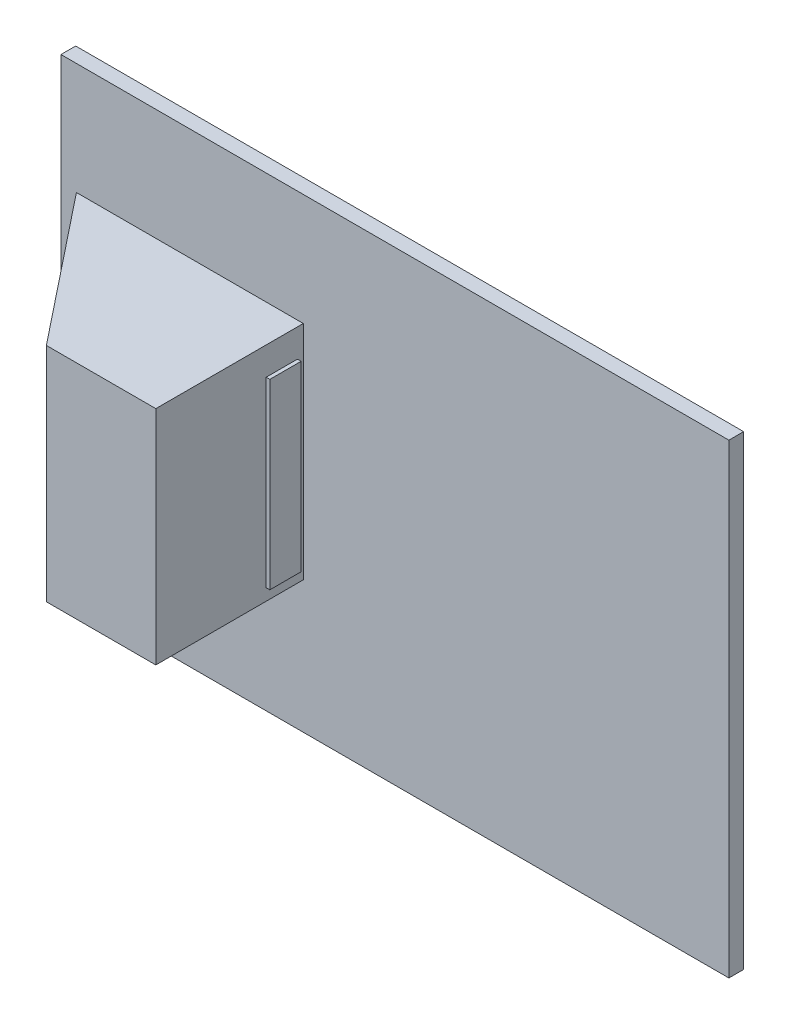
SolidWorks part; units mm, degrees
ref_plane "Front Plane" through (0, 0, 0) normal (0, 0, 1) x (1, 0, 0)
ref_plane "Top Plane" through (0, 0, 0) normal (0, 1, 0) x (1, 0, 0)
ref_plane "Right Plane" through (0, 0, 0) normal (1, 0, 0) x (0, 0, -1)
sketch "Sketch1" plane through (0, 0, 0) normal (0, 0, 1) x (1, 0, 0)
  line L1 (-83.6964, -45.2831) -> (2.5697, -45.2831)
  line L2 (-83.6964, -45.2831) -> (-83.6964, 12.5794)
  line L3 (-83.6964, 12.5794) -> (2.5697, 12.5794)
  line L4 (2.5697, -45.2831) -> (2.5697, 12.5794)
  line L5 (-83.6964, -45.2831) -> (2.5697, 12.5794) construction
  line L6 (-83.6964, 12.5794) -> (2.5697, -45.2831) construction
  point P0 (-40.5634, -16.3519)
  point P5 (2.5697, -48.5767)
extrude "Boss-Extrude1" add sketch "Sketch1" along normal blind 5
sketch "Sketch2" plane through (0, 0, 0) normal (0, 0, -1) x (-1, 0, 0)
  line L1 (50.5486, -38.5474) -> (14.2877, -38.5474)
  line L2 (50.5486, -38.5474) -> (50.5486, 6.6921)
  line L3 (50.5486, 6.6921) -> (14.2877, 6.6921)
  line L4 (14.2877, -38.5474) -> (14.2877, 6.6921)
  line L5 (50.5486, -38.5474) -> (14.2877, 6.6921) construction
  line L6 (50.5486, 6.6921) -> (14.2877, -38.5474) construction
  line L7 (49.8095, -37.7028) -> (15.0267, -37.7028)
  line L8 (49.8095, -37.7028) -> (49.8095, 5.8475)
  line L9 (49.8095, 5.8475) -> (15.0267, 5.8475)
  line L10 (15.0267, -37.7028) -> (15.0267, 5.8475)
  line L11 (49.8095, -37.7028) -> (15.0267, 5.8475) construction
  line L12 (49.8095, 5.8475) -> (15.0267, -37.7028) construction
  point P0 (32.4181, -15.9276)
  point P5 (29.0156, -12.5739)
  point P6 (32.4181, -15.9276)
  point P11 (31.5127, -12.7779)
  point P12 (31.8702, -14.0102)
  point P13 (32.3017, -17.6957)
  point P14 (32.6138, -14.9651)
  point P15 (32.4181, -15.9276)
extrude "Boss-Extrude2" add sketch "Sketch2" along normal blind 1
sketch "Sketch3" plane through (0, 0, 0) normal (0, 0, -1) x (-1, 0, 0)
  circle A0 centre (5.8472, -15.8094) radius 3.5601
  point P2 (0, 0)
extrude "Boss-Extrude3" add sketch "Sketch3" along normal blind 1
sketch "Sketch4" plane through (0, 0, -1) normal (0, 0, -1) x (-1, 0, 0)
  line L0 (7.4982, -13.5037) -> (7.4299, -14.2268)
  line L1 (7.3138, -18.3414) -> (7.3192, -17.6008)
  arc A0 (7.4982, -13.5037) -> (7.3138, -18.3414) centre (5.955, -15.8672) ccw
  arc A1 (7.4299, -14.2268) -> (7.3192, -17.6008) centre (5.955, -15.8672) ccw
  point P1 (0, 0)
extrude "Cut-Extrude2" cut sketch "Sketch4" against normal blind 0.5
sketch "Sketch5" plane through (0, 0, -1) normal (0, 0, -1) x (-1, 0, 0)
  line L0 (8.3401, -15.4929) -> (5.464, -15.4382)
  line L1 (8.3401, -16.1787) -> (5.464, -16.2334)
  arc A0 (8.3401, -16.1787) -> (8.3401, -15.4929) centre (8.3401, -15.8358) ccw
  arc A1 (5.464, -15.4382) -> (5.464, -16.2334) centre (5.464, -15.8358) ccw
extrude "Cut-Extrude3" cut sketch "Sketch5" against normal blind 0.5
sketch "Sketch11" plane through (0, 0, 5) normal (0, 0, 1) x (1, 0, 0)
  line L1 (-85.049, -48.3572) -> (5.5329, -48.3572)
  line L2 (-85.049, -48.3572) -> (-85.049, 14.8126)
  line L3 (-85.049, 14.8126) -> (5.5329, 14.8126)
  line L4 (5.5329, -48.3572) -> (5.5329, 14.8126)
  line L5 (-85.049, -48.3572) -> (5.5329, 14.8126) construction
  line L6 (-85.049, 14.8126) -> (5.5329, -48.3572) construction
  point P0 (-39.7581, -16.7723)
extrude "Boss-Extrude4" add sketch "Sketch11" along normal blind 2
sketch "Sketch12" plane through (2.5697, 0, 0) normal (1, 0, 0) x (0, 0, -1)
  line L0 (-5.0495, 12.5555) -> (1.3768, 8.6378)
  line L1 (1.3768, 8.6378) -> (1.4949, 17.885)
  line L2 (1.4949, 17.885) -> (-5.0495, 12.5555)
  point P0 (-5.0495, 12.5555)
extrude "Cut-Extrude11" cut sketch "Sketch12" against normal through all
sketch "Sketch14" plane through (-85.049, 0, 0) normal (-1, 0, 0) x (0, 0, 1)
  line L0 (5, -45.2349) -> (-1.3308, -41.1782)
  line L1 (5, 12.5253) -> (5, -48.3572) construction
  line L2 (-1.3308, -41.1782) -> (-1.6233, -49.506)
  line L3 (-1.6233, -49.506) -> (5, -45.2349)
  point P4 (5, -45.2349)
extrude "Cut-Extrude15" cut sketch "Sketch14" against normal through all
sketch "Sketch15" plane through (0, -48.3572, 0) normal (0, -1, 0) x (-1, 0, 0)
  line L0 (-2.5596, -5) -> (1.7788, 1.2395)
  line L1 (85.049, -5) -> (-5.5329, -5) construction
  line L2 (1.7788, 1.2395) -> (-4.0713, 1.1275)
  line L3 (-4.0713, 1.1275) -> (-2.5596, -5)
  point P4 (-2.5263, -5)
  point P8 (-2.5596, -5)
extrude "Cut-Extrude18" cut sketch "Sketch15" against normal through all
sketch "Sketch19" plane through (0, -48.3572, 0) normal (0, -1, 0) x (-1, 0, 0)
  line L0 (83.7172, -5) -> (87.2746, 1.6454)
  line L1 (85.049, -5) -> (-5.5329, -5) construction
  line L2 (87.2746, 1.6454) -> (78.5287, 2.7469)
  line L3 (78.5287, 2.7469) -> (83.7172, -5)
extrude "Cut-Extrude21" cut sketch "Sketch19" against normal through all
sketch "Sketch22" plane through (0, 0, 7) normal (0, 0, 1) x (1, 0, 0)
  line L1 (-82.9526, -0.3433) -> (-52.184, -0.3433)
  line L2 (-82.9526, -0.3433) -> (-82.9526, -30.4515)
  line L3 (-82.9526, -30.4515) -> (-52.184, -30.4515)
  line L4 (-52.184, -0.3433) -> (-52.184, -30.4515)
  line L5 (-82.9526, -0.3433) -> (-52.184, -30.4515) construction
  line L6 (-82.9526, -30.4515) -> (-52.184, -0.3433) construction
  point P0 (-67.5683, -15.3974)
extrude "Boss-Extrude9" add sketch "Sketch22" along normal blind 20
sketch "Sketch23" plane through (-55.4815, 0, -37.1587) normal (-0.8309, 0, -0.5565) x (-0.5565, 0, 0.8309)
  line L0 (50.7032, -28.438) -> (50.7032, -4.3391)
  line L1 (50.7032, 12.5064) -> (50.7032, -45.2151) construction
  line L2 (50.7032, -4.3391) -> (35.7393, -4.3391)
  line L3 (35.7393, -4.3391) -> (35.7393, -28.6863)
  line L4 (35.7393, -28.6863) -> (50.7032, -28.438)
  point P4 (39.3795, -28.6259)
extrude "Cut-Extrude25" cut sketch "Sketch23" against normal blind 30
sketch "Sketch24" plane through (0, 0, 0) normal (0, 0, -1) x (-1, 0, 0)
  line L0 (80.3685, -4.3391) -> (64.2248, -4.3391) construction
  line L1 (53.8212, -28.6863) -> (64.2248, -28.6863)
  line L2 (53.8212, -28.6863) -> (53.8212, -4.3391)
  line L3 (53.8212, -4.3391) -> (64.2248, -4.3391)
  line L4 (64.2248, -28.6863) -> (64.2248, -4.3391)
  line L5 (53.8212, -28.6863) -> (64.2248, -4.3391) construction
  line L6 (53.8212, -4.3391) -> (64.2248, -28.6863) construction
  line L7 (64.2248, -4.3391) -> (64.2248, -28.6863) construction
  point P0 (59.023, -16.5127)
extrude "Cut-Extrude27" cut sketch "Sketch24" against normal blind 7
sketch "Sketch25" plane through (0, -30.4515, 0) normal (0, -1, 0) x (-1, 0, 0)
  line L0 (67.027, -27) -> (82.9526, -7)
  line L1 (82.9526, -27) -> (52.184, -27) construction
  line L2 (82.9526, -7) -> (82.9526, -27)
  line L3 (82.9526, -27) -> (82.9526, -7) construction
  line L4 (82.9526, -27) -> (67.027, -27)
  point P5 (82.9526, -27)
extrude "Cut-Extrude29" cut sketch "Sketch25" against normal through all
sketch "Sketch26" plane through (-28.2149, 0, 42.1276) normal (0.5565, 0, -0.8309) x (-0.8309, 0, -0.5565)
  line L0 (54.7061, -26.9497) -> (51.42, -27.0426)
  line L1 (51.42, -27.0426) -> (49.1981, -24.943)
  line L2 (49.1981, -24.943) -> (49.1134, -21.9477)
  line L3 (49.1134, -21.9477) -> (51.379, -19.9792)
  line L4 (51.379, -19.9792) -> (54.3761, -19.7757)
  line L5 (54.3761, -19.7757) -> (56.7869, -21.3756)
  line L6 (56.7869, -21.3756) -> (56.7869, -24.7523)
  line L7 (56.7869, -24.7523) -> (54.7061, -26.9497)
  line L8 (54.7061, -26.4154) -> (51.5118, -26.5172)
  line L9 (51.5118, -26.5172) -> (49.6724, -24.7913)
  line L10 (49.6724, -24.7913) -> (49.5843, -22.0272)
  line L11 (49.5843, -22.0272) -> (51.5118, -20.3421)
  line L13 (54.292, -20.113) -> (56.4421, -21.5046)
  line L14 (56.4421, -21.5046) -> (56.4421, -24.6328)
  line L15 (56.4421, -24.6328) -> (54.7061, -26.4154)
  line L16 (54.292, -20.113) -> (51.4865, -20.3421)
extrude "Boss-Extrude12" add sketch "Sketch26" along normal blind 0.5
sketch "Sketch27" plane through (-27.9367, 0, 41.7122) normal (0.5565, 0, -0.8309) x (-0.8309, 0, -0.5565)
  line L0 (54.4646, -26.3342) -> (51.6468, -26.4613)
  line L1 (51.6468, -26.4613) -> (49.7838, -24.7591)
  line L2 (49.7838, -24.7591) -> (49.7838, -22.033)
  line L3 (49.7838, -22.033) -> (51.4884, -20.6267)
  line L4 (51.4884, -20.6267) -> (54.0987, -20.567)
  line L5 (54.0987, -20.567) -> (56.1639, -21.7042)
  line L6 (56.1639, -21.7042) -> (56.2319, -24.6811)
  line L7 (56.2319, -24.6811) -> (54.4646, -26.3342)
  line L8 (54.3202, -25.7184) -> (51.7276, -25.7776)
  line L9 (51.7276, -25.7776) -> (50.5704, -24.5406)
  line L10 (50.5704, -24.5406) -> (50.4628, -22.1543)
  line L11 (50.4628, -22.1543) -> (51.4425, -21.2379)
  line L12 (51.4425, -21.2379) -> (54.0133, -21.2379)
  line L13 (54.0133, -21.2379) -> (55.475, -22.0626)
  line L14 (55.475, -22.0626) -> (55.475, -24.5406)
  line L15 (55.475, -24.5406) -> (54.3202, -25.7184)
  point P11 (55.6709, -24.7402)
  point P17 (51.4521, -21.229)
  point P18 (54.0133, -21.2379)
  point P19 (50.5704, -24.5406)
extrude "Cut-Extrude30" cut sketch "Sketch27" against normal blind 0.5
sketch "Sketch28" plane through (-52.184, 0, 0) normal (1, 0, 0) x (0, 0, -1)
  line L1 (-7.7943, -4.1368) -> (-12.0375, -4.1368)
  line L2 (-7.7943, -4.1368) -> (-7.7943, -28.8565)
  line L3 (-7.7943, -28.8565) -> (-12.0375, -28.8565)
  line L4 (-12.0375, -4.1368) -> (-12.0375, -28.8565)
  line L5 (-7.7943, -4.1368) -> (-12.0375, -28.8565) construction
  line L6 (-7.7943, -28.8565) -> (-12.0375, -4.1368) construction
  point P0 (-9.9159, -16.4967)
extrude "Boss-Extrude13" add sketch "Sketch28" along normal blind 0.5
sketch "Sketch30" plane through (-28.2149, 0, 42.1276) normal (0.5565, 0, -0.8309) x (-0.8309, 0, -0.5565)
  line L0 (39.741, -18.4923) -> (39.4768, -15.4766)
  line L1 (39.4768, -15.4766) -> (41.6727, -13.4395)
  line L2 (41.6727, -13.4395) -> (44.994, -13.0953)
  line L3 (44.994, -13.0953) -> (47.5825, -14.9189)
  line L4 (47.5825, -14.9189) -> (47.5825, -17.5566)
  line L5 (47.5825, -17.5566) -> (45.5971, -19.8398)
  line L6 (45.5971, -19.8398) -> (42.2786, -20.1305)
  line L7 (42.2786, -20.1305) -> (39.741, -18.4923)
  line L8 (42.7534, -19.5576) -> (40.2187, -17.9152)
  line L9 (40.2187, -17.9152) -> (40.0475, -15.6187)
  line L10 (40.0475, -15.6187) -> (41.8581, -13.9959)
  line L11 (41.8581, -13.9959) -> (44.6411, -13.7001)
  line L12 (44.6411, -13.7001) -> (47.0086, -15.2342)
  line L13 (47.0086, -15.2342) -> (47.0876, -17.3469)
  line L14 (47.0876, -17.3469) -> (45.2147, -19.3741)
  line L15 (45.2147, -19.3741) -> (42.7534, -19.5576)
  point P2 (45.2147, -19.3741)
  point P18 (45.5971, -19.8398)
  point P19 (42.7037, -19.5576)
extrude "Boss-Extrude14" add sketch "Sketch30" along normal blind 0.5
sketch "Sketch31" plane through (-28.2149, 0, 42.1276) normal (0.5565, 0, -0.8309) x (-0.8309, 0, -0.5565)
  line L0 (42.8579, -19.0017) -> (40.9087, -17.7098)
  line L1 (40.9087, -17.7098) -> (40.7983, -15.9356)
  line L2 (40.7983, -15.9356) -> (42.2062, -14.4864)
  line L3 (42.2062, -14.4864) -> (44.0287, -14.2678)
  line L4 (44.0287, -14.2678) -> (46.1553, -15.6773)
  line L5 (46.1553, -15.6773) -> (46.2514, -17.2226)
  line L6 (46.2514, -17.2226) -> (44.5885, -18.9343)
  line L7 (44.5885, -18.9343) -> (42.8579, -19.0017)
  point P2 (42.937, -18.9986)
  point P9 (40.7614, -17.4233)
extrude "Boss-Extrude15" add sketch "Sketch31" along normal blind 0.5
sketch "Sketch33" plane through (-28.2149, 0, 42.1276) normal (0.5565, 0, -0.8309) x (-0.8309, 0, -0.5565)
  line L0 (53.5036, -12.1793) -> (50.3513, -12.1793)
  line L1 (53.5036, -5.7866) -> (50.2502, -5.7866)
  line L2 (53.5036, -12.1793) -> (55.5149, -10.4174)
  line L3 (55.5149, -10.4174) -> (55.5149, -7.3707)
  line L4 (55.5149, -7.3707) -> (53.5036, -5.7866)
  line L5 (50.3513, -12.1793) -> (48.1508, -10.2126)
  line L6 (48.1508, -10.2126) -> (48.1508, -7.1561)
  line L7 (48.1508, -7.1561) -> (50.2502, -5.7866)
  line L8 (53.5036, -11.5928) -> (50.5381, -11.5928)
  line L9 (50.5381, -11.5928) -> (48.7427, -9.9711)
  line L10 (48.7427, -9.9711) -> (48.6105, -7.3707)
  line L11 (48.6105, -7.3707) -> (50.2502, -6.3087)
  line L12 (50.2502, -6.3087) -> (53.3239, -6.3087)
  line L13 (53.3239, -6.3087) -> (54.9664, -7.5403)
  line L14 (54.9664, -7.5403) -> (54.9664, -10.4174)
  line L15 (54.9664, -10.4174) -> (53.5036, -11.5928)
extrude "Boss-Extrude16" add sketch "Sketch33" along normal blind 0.5
sketch "Sketch34" plane through (-28.2149, 0, 42.1276) normal (0.5565, 0, -0.8309) x (-0.8309, 0, -0.5565)
  line L0 (53.1065, -10.9168) -> (50.7972, -10.9168)
  line L1 (50.7972, -10.9168) -> (49.2381, -9.7583)
  line L2 (49.2381, -9.7583) -> (49.2381, -7.7183)
  line L3 (49.2381, -7.7183) -> (50.3642, -6.7724)
  line L4 (50.3642, -6.7724) -> (52.9303, -6.7724)
  line L5 (52.9303, -6.7724) -> (54.1875, -7.7448)
  line L6 (54.1875, -7.7448) -> (54.1875, -9.9905)
  line L7 (54.1875, -9.9905) -> (53.1065, -10.9168)
  point P5 (54.1875, -9.9905)
  point P9 (49.4822, -7.815)
  point P10 (52.9303, -6.7724)
  point P11 (49.2412, -7.7448)
  point P12 (49.2381, -9.7583)
extrude "Boss-Extrude17" add sketch "Sketch34" along normal blind 0.5
sketch "Sketch35" plane through (-28.2149, 0, 42.1276) normal (0.5565, 0, -0.8309) x (-0.8309, 0, -0.5565)
  line L0 (64.7134, -17.1204) -> (64.7134, -13.8698)
  line L1 (64.7134, -13.8698) -> (62.5655, -12.2617)
  line L2 (62.5655, -12.2617) -> (58.9579, -12.2617)
  line L3 (64.7134, -17.1204) -> (62.5229, -19.1048)
  line L4 (62.5229, -19.1048) -> (59.3824, -19.1048)
  line L5 (59.3824, -19.1048) -> (56.8589, -17.1993)
  line L6 (56.8589, -17.1993) -> (56.8589, -14.2019)
  line L7 (56.8589, -14.2019) -> (58.9579, -12.2617)
  line L8 (62.3869, -18.4035) -> (59.3824, -18.4035)
  line L9 (59.3824, -18.4035) -> (57.5666, -17.0465)
  line L10 (57.5666, -17.0465) -> (57.5666, -14.5319)
  line L11 (57.5666, -14.5319) -> (59.0471, -12.8652)
  line L12 (59.0471, -12.8652) -> (62.5655, -12.8652)
  line L13 (62.5655, -12.8652) -> (63.9381, -13.891)
  line L14 (63.9381, -13.891) -> (63.9381, -16.9379)
  line L15 (63.9381, -16.9379) -> (62.3869, -18.4035)
  point P9 (59.0471, -12.8652)
  point P17 (62.5655, -12.8652)
  point P18 (59.7921, -18.2067)
  point P19 (59.3824, -19.1048)
  point P20 (56.8589, -17.1993)
  point P21 (57.5666, -17.0013)
  point P22 (59.3824, -18.4035)
  point P23 (64.7134, -17.1204)
extrude "Boss-Extrude18" add sketch "Sketch35" along normal blind 0.5
sketch "Sketch36" plane through (-28.2149, 0, 42.1276) normal (0.5565, 0, -0.8309) x (-0.8309, 0, -0.5565)
  line L0 (61.8697, -17.4964) -> (59.9308, -17.4964)
  line L1 (59.9308, -17.4964) -> (58.7161, -16.6958)
  line L2 (58.7161, -16.6958) -> (58.52, -14.7296)
  line L3 (58.52, -14.7296) -> (59.3629, -13.4509)
  line L4 (59.3629, -13.4509) -> (61.6665, -13.4509)
  line L5 (61.6665, -13.4509) -> (62.906, -14.2679)
  line L6 (62.906, -14.2679) -> (62.906, -16.3755)
  line L7 (62.906, -16.3755) -> (61.8697, -17.4964)
  point P7 (61.3205, -13.4509)
  point P9 (61.8727, -17.4931)
  point P10 (59.7324, -17.4964)
  point P11 (58.5071, -16.3755)
  point P12 (58.5071, -14.69)
  point P13 (58.52, -14.7296)
  point P14 (58.7161, -16.6958)
extrude "Boss-Extrude19" add sketch "Sketch36" along normal blind 0.5
